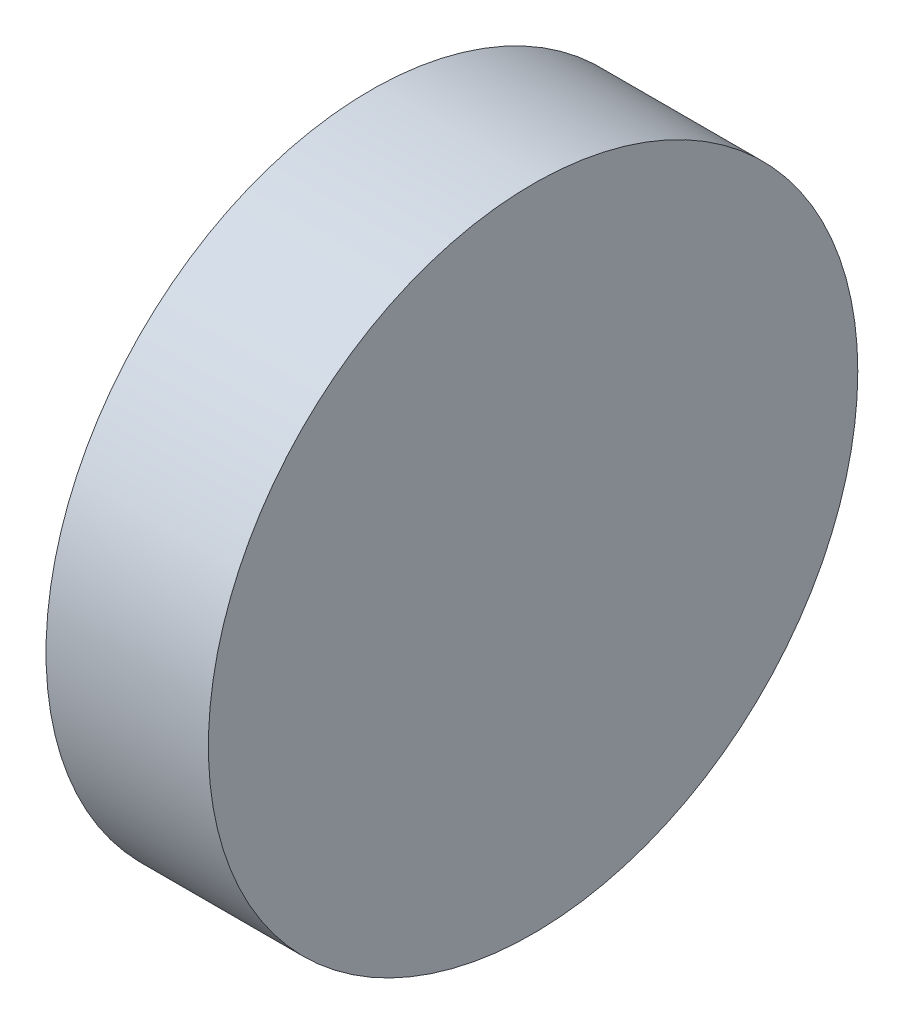
SolidWorks part; units mm, degrees
ref_plane "Front Plane" through (0, 0, 0) normal (0, 0, 1) x (1, 0, 0)
ref_plane "Top Plane" through (0, 0, 0) normal (0, 1, 0) x (1, 0, 0)
ref_plane "Right Plane" through (0, 0, 0) normal (1, 0, 0) x (0, 0, -1)
sketch "Sketch1" plane through (0, 0, 0) normal (1, 0, 0) x (0, 0, -1)
  circle A0 centre (0, 0) radius 20
  dimension "D1" = 40
extrude "Boss-Extrude1" add sketch "Sketch1" along normal blind 10
hole_wizard "M2x0.4 Tapped Hole1" positions "Sketch2" profile "Sketch3" tap size "M2x0.4" standard "ANSI Metric"
sketch "Sketch2" plane through (0, 0, 0) normal (-1, 0, 0) x (0, 0, 1)
  point P5 (0, -5)
  point P8 (0, 0)
  point P9 (0, 0)
sketch "Sketch3" plane through (0, -5, 0) normal (0, 1, 0) x (0, 0, 1)
  line L0 (0, 0) -> (0, 5.6807)
  line L1 (0, 5.6807) -> (0.8, 5.2)
  line L2 (0.8, 5.2) -> (0.8, 0.225)
  line L3 (0.8, 0.225) -> (1.025, 0)
  line L5 (1.025, 0) -> (0, 0)
  line L6 (-0.8, 0.225) -> (-1.025, 0) construction
  line L10 (0, 5.6807) -> (-0.8, 5.2) construction
  line L11 (0, -6.35) -> (0, 107.95) construction
  dimension "Tap Drill Dia." = 1.6
  dimension "Tap Drill Depth" = 5.2
  dimension "Near C'Sink Dia." = 2.05
  dimension "Near C'Sink Angle" = 90
  dimension "Drill Angle" = 118
cosmetic thread "Hole Thread1"
